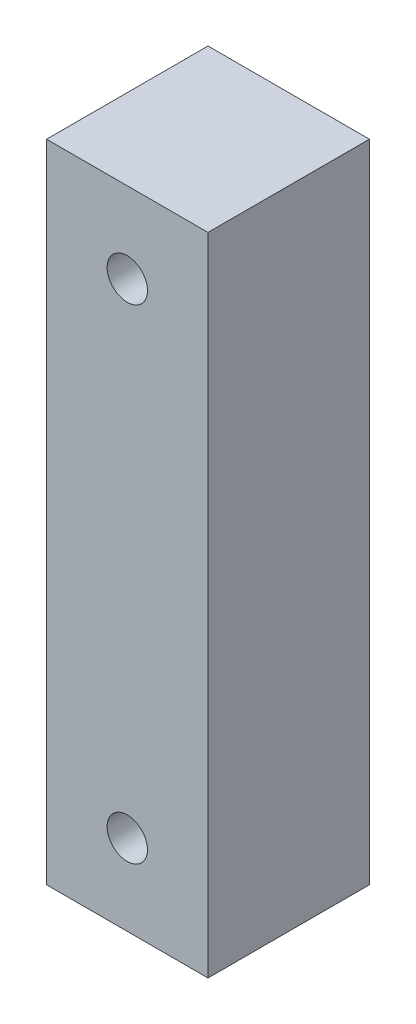
SolidWorks part; units mm, degrees
material "Oak"
ref_plane "Front" through (0, 0, 0) normal (0, 0, 1) x (1, 0, 0)
ref_plane "Top" through (0, 0, 0) normal (0, 1, 0) x (1, 0, 0)
ref_plane "Right" through (0, 0, 0) normal (1, 0, 0) x (0, 0, -1)
sketch "Sketch1" plane through (0, 0, 0) normal (0, 0, 1) x (1, 0, 0)
  line L1 (0, 0) -> (38.1, 0)
  line L2 (0, 0) -> (0, 152.4)
  line L3 (0, 152.4) -> (38.1, 152.4)
  line L4 (38.1, 0) -> (38.1, 152.4)
  dimension "D1" = 38.1
  dimension "D2" = 152.4
extrude "Boss-Extrude1" add sketch "Sketch1" along normal blind 38.1
sketch "Sketch2" plane through (0, 0, 38.1) normal (0, 0, 1) x (1, 0, 0)
  line L0 (0, 152.4) -> (0, 0) construction
  line L1 (38.1, 152.4) -> (0, 152.4) construction
  circle A0 centre (19.05, 133.35) radius 4.7625
  dimension "D1" = 19.05
  dimension "D3" = 9.525
  dimension "D2" = 19.05
extrude "Cut-Extrude1" cut sketch "Sketch2" against normal through all
sketch "Sketch3" plane through (0, 0, 38.1) normal (0, 0, 1) x (1, 0, 0)
  line L0 (0, 0) -> (38.1, 0) construction
  line L2 (0, 152.4) -> (0, 0) construction
  circle A0 centre (19.05, 19.05) radius 4.7625
  dimension "D3" = 9.525
  dimension "D1" = 19.05
  dimension "D2" = 19.05
extrude "Cut-Extrude2" cut sketch "Sketch3" against normal through all
